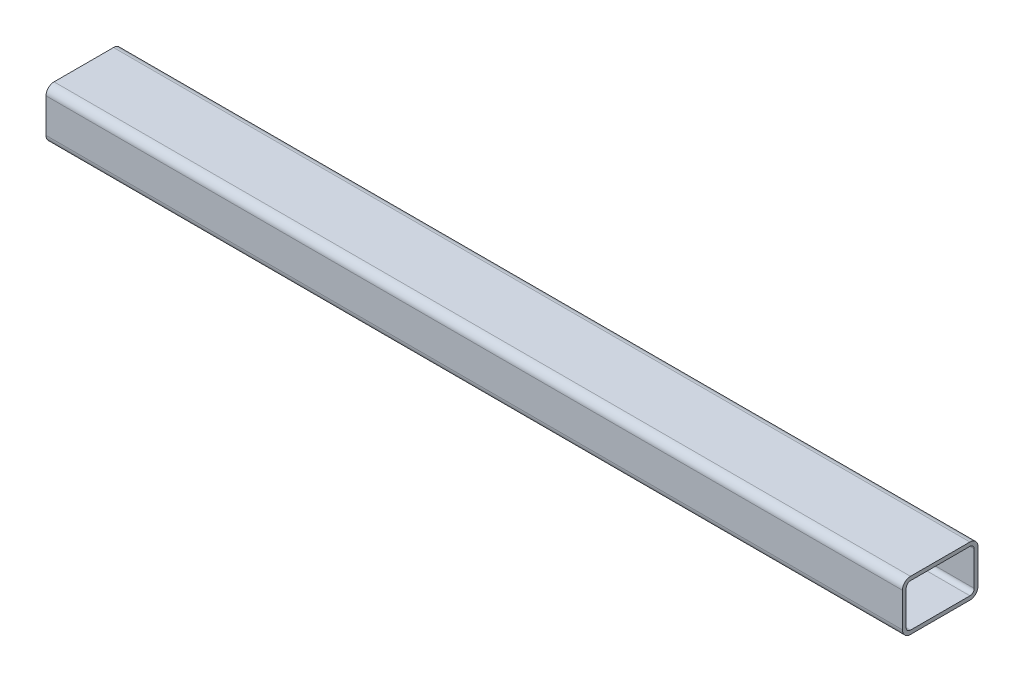
SolidWorks part; units mm, degrees
ref_plane "Front Plane" through (0, 0, 0) normal (0, 0, 1) x (1, 0, 0)
ref_plane "Top Plane" through (0, 0, 0) normal (0, 1, 0) x (1, 0, 0)
ref_plane "Right Plane" through (0, 0, 0) normal (1, 0, 0) x (0, 0, -1)
sketch "Sketch12" plane through (0, 0, 0) normal (0, 0, 1) x (1, 0, 0)
  line L0 (-340, 0) -> (340, 0)
  dimension "D1" = 680
other "Rectangular tube - configured 60 X 40 X 3.2(2)"
ref_plane "Plane5" through (-340, 0, 0) normal (1, 0, 0) x (0, 1, 0)
sketch "Sketch1" plane through (-340, 0, 0) normal (1, 0, 0) x (0, 1, 0)
  line L0 (-13.6, -27) -> (13.6, -27)
  line L1 (-17, -23.6) -> (-17, 23.6)
  line L2 (13.6, 27) -> (-13.6, 27)
  line L3 (17, 23.6) -> (17, -23.6)
  line L4 (-13.6, -30) -> (13.6, -30)
  line L5 (-20, -23.6) -> (-20, 23.6)
  line L6 (13.6, 30) -> (-13.6, 30)
  line L7 (20, 23.6) -> (20, -23.6)
  arc A0 (20, 23.6) -> (13.6, 30) centre (13.6, 23.6) ccw
  arc A1 (13.6, -30) -> (20, -23.6) centre (13.6, -23.6) ccw
  arc A2 (-20, -23.6) -> (-13.6, -30) centre (-13.6, -23.6) ccw
  arc A3 (-13.6, 30) -> (-20, 23.6) centre (-13.6, 23.6) ccw
  arc A4 (-13.6, 27) -> (-17, 23.6) centre (-13.6, 23.6) ccw
  arc A5 (17, 23.6) -> (13.6, 27) centre (13.6, 23.6) ccw
  arc A6 (13.6, -27) -> (17, -23.6) centre (13.6, -23.6) ccw
  arc A7 (-17, -23.6) -> (-13.6, -27) centre (-13.6, -23.6) ccw
  point P0 (0, 30)
  point P1 (20, 0)
  point P2 (0, -30)
  point P3 (-20, 0)
  point P4 (-20, 30)
  point P5 (20, 30)
  point P6 (20, -30)
  point P7 (-20, -30)
  point P8 (0, 0)
  point P33 (0, 0)
  dimension "D1" = 6.4
  dimension "Thickness" = 3
  dimension "V_leg" = 60
  dimension "H_leg" = 40
sketch "Sketch13" [suppressed] plane through (0, 20, 0) normal (0, 1, 0) x (1, 0, 0)
  line L0 (340, -23.6) -> (-340, -23.6) construction
  line L2 (-146.967, -23.6) -> (-148.4014, -20.9651)
  line L8 (-77.9742, -23.6) -> (-75.3275, -22.1877)
  spline S3 degree 5 poles (-1495.764, 2640.3207) (-54.553, -70.7255) (-171.9433, 151.7914) (-124.9932, 64.4419) (-90.2809, -0.4141) (-58.6075, -59.9528) (-57.0332, -62.9132) (-50.8072, -74.6241) (-44.8114, -85.9169) (-40.4158, -94.2031) (-34.6955, -104.9963) (-29.2334, -115.3147) (-27.9081, -117.8187) (-6.1309, -158.9794) (9.5785, -188.8602) (45.0801, -256.14) (-220.7139, 245.2426) (1397.5545, -2793.1722) knots -593.265604 -593.265604 -593.265604 -593.265604 -593.265604 -593.265604 111.1559 111.1559 111.1559 148.187473 148.187473 148.187473 259.213082 259.213082 259.213082 296.361016 296.361016 296.361016 871.835515 871.835515 871.835515 871.835515 871.835515 871.835515 weights 1 1 1 1 1 1 1 1 1 1 1 1 1 1 1 1 1 1 only from (-86.3756, -7.8668) to (-13.0552, -145.9241) construction
  spline S4 degree 5 poles (-2891.5119, 1081.1487) (142.8151, 263.2412) (-50.9894, -103.5827) (-137.1222, -44.038) (-122.2566, -1.9712) (-100.2843, 0.1197) (-99.3189, 0.1331) (-97.3976, 0.0041) (-95.5308, -0.4278) (-94.6201, -0.7173) (-92.4201, -1.6144) (-90.4526, -2.9143) (-89.3782, -3.8223) (-82.0749, -11.5923) (-82.3869, -24.5188) (-91.346, -33.6867) (-134.8623, 15.5931) (1509.7915, -2547.4591) knots -234.55056 -234.55056 -234.55056 -234.55056 -234.55056 -234.55056 11.238702 11.238702 11.238702 22.477403 22.477403 22.477403 33.716105 33.716105 33.716105 50.576238 50.576238 50.576238 162.81808 162.81808 162.81808 162.81808 162.81808 162.81808 weights 1 1 1 1 1 1 1 1 1 1 1 1 1 1 1 1 1 1 only from (-106.705, -1.7175) to (-86.3756, -7.8668) construction
  spline S5 degree 5 poles (-2864.2984, -1509.6725) (-276.3602, -94.7125) (-345.1875, -132.0922) (-303.3863, -109.1241) (-254.2395, -82.166) (-202.7549, -54.0301) (-200.2583, -52.6659) (-192.7828, -48.5821) (-185.2556, -44.4723) (-180.2173, -41.7225) (-170.1251, -36.2168) (-159.9585, -30.6752) (-154.883, -27.9099) (-33.4803, 38.2018) (92.7831, 106.1794) (200.5046, 162.8586) (275.2579, 193.0138) (2464.1913, 1543.5518) knots -550.303408 -550.303408 -550.303408 -550.303408 -550.303408 -550.303408 62.724665 62.724665 62.724665 93.899246 93.899246 93.899246 155.902112 155.902112 155.902112 217.55572 217.55572 217.55572 1627.442536 1627.442536 1627.442536 1627.442536 1627.442536 1627.442536 weights 1 1 1 1 1 1 1 1 1 1 1 1 1 1 1 1 1 1 only from (-232.4669, -70.2789) to (-106.705, -1.7175) construction
  spline S6 degree 5 poles (-86.3756, -7.8668) (-84.6836, -11.0331) (-82.9975, -14.1895) (-81.3168, -17.337) (-79.6421, -20.4743) (-77.9742, -23.6) knots 0 0 0 0 0 0 37.291521 37.291521 37.291521 37.291521 37.291521 37.291521 weights 1 1 1 1 1 1
  spline S7 degree 5 poles (-106.705, -1.7175) (-105.8638, -1.2611) (-104.1041, -0.4804) (-102.2198, 0.0152) (-100.2796, 0.1976) (-97.3976, 0.0041) (-95.5308, -0.4278) (-94.6201, -0.7173) (-92.4201, -1.6144) (-90.4526, -2.9143) (-89.3782, -3.8223) (-88.1065, -5.1752) (-87.0657, -6.6845) (-86.8204, -7.0708) (-86.5903, -7.4651) (-86.3756, -7.8668) knots 0 0 0 0 0 0 11.238702 22.477403 22.477403 22.477403 33.716105 33.716105 33.716105 50.576238 50.576238 50.576238 56.195589 56.195589 56.195589 56.195589 56.195589 56.195589 weights 1 1 1 1 1 1 1 1 1 1 1 1 1 1 1 1
  spline S8 degree 5 poles (-146.967, -23.6) (-146.514, -23.3534) (-146.061, -23.1068) (-145.6079, -22.8602) (-137.585, -18.4931) (-129.5409, -14.118) (-121.9372, -9.9855) (-114.3244, -5.8515) (-106.705, -1.7175) knots 212.071321 212.071321 212.071321 212.071321 212.071321 212.071321 217.55572 217.55572 217.55572 309.169876 309.169876 309.169876 309.169876 309.169876 309.169876 weights 1 1 1 1 1 1 1 1 1
  spline S9 degree 1 poles (-148.4014, -20.9651) (-108.1357, 0.9194) knots 0 0 1 1 construction
  spline S10 degree 3 poles (-148.4014, -20.9651) (-145.0557, -19.1438) (-138.3692, -15.5051) (-128.3056, -10.033) (-118.2289, -4.5585) (-111.4994, -0.9057) (-108.1357, 0.9194) knots 212.071321 212.071321 212.071321 212.071321 236.34596 260.620598 284.895237 309.169876 309.169876 309.169876 309.169876
  spline S11 degree 1 poles (-108.1357, 0.9194) (-83.7297, -6.4528) knots 0 0 1 1 construction
  spline S12 degree 3 poles (-108.1357, 0.9194) (-106.0371, 2.058) (-101.326, 3.5036) (-94.0109, 2.7036) (-87.7202, -0.8096) (-84.8056, -4.4396) (-83.7297, -6.4528) knots 0 0 0 0 14.048897 28.097794 42.146692 56.195589 56.195589 56.195589 56.195589
  spline S13 degree 1 poles (-83.7297, -6.4528) (-75.3275, -22.1877) knots 0 0 1 1 construction
  spline S14 degree 3 poles (-83.7297, -6.4528) (-83.0258, -7.7702) (-81.6164, -10.4081) (-79.5128, -14.3468) (-77.4147, -18.2765) (-76.0238, -20.8828) (-75.3275, -22.1877) knots 0 0 0 0 9.32288 18.64576 27.968641 37.291521 37.291521 37.291521 37.291521
  dimension "D1" = 3
extrude "Boss-Extrude1" [suppressed] add sketch "Sketch13" along normal blind 10 separate body contours S14 S12 S10 L2 S8 S7 S6 L8
mirror "Mirror3" [suppressed] about plane through (0, 0, 0) normal (1, 0, 0)
